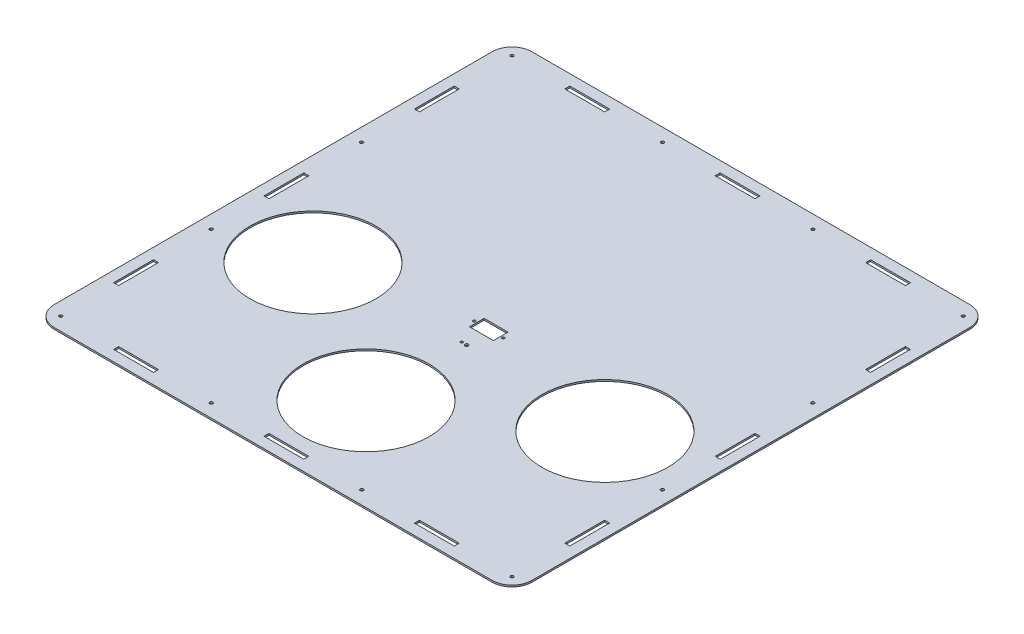
SolidWorks part; units mm, degrees
ref_plane "Front Plane" through (0, 0, 0) normal (0, 0, 1) x (1, 0, 0)
ref_plane "Top Plane" through (0, 0, 0) normal (0, 1, 0) x (1, 0, 0)
ref_plane "Right Plane" through (0, 0, 0) normal (1, 0, 0) x (0, 0, -1)
sketch "Sketch1" plane through (0, 0, 0) normal (0, 1, 0) x (1, 0, 0)
  line L1 (-228.6, -228.6) -> (228.6, -228.6)
  line L2 (-228.6, -228.6) -> (-228.6, 228.6)
  line L3 (-228.6, 228.6) -> (228.6, 228.6)
  line L4 (228.6, -228.6) -> (228.6, 228.6)
  line L5 (-228.6, -228.6) -> (228.6, 228.6) construction
  line L6 (-228.6, 228.6) -> (228.6, -228.6) construction
  point P0 (0, 0)
  dimension "D1" = 457.2
extrude "Main Plate" add sketch "Sketch1" along normal blind 1.5875
sketch "Sketch2" plane through (0, 1.5875, 0) normal (0, 1, 0) x (1, 0, 0)
  line L0 (228.6, 0) -> (-228.6, 0) construction
  line L1 (-228.6, 228.6) -> (-228.6, -228.6) construction
  line L2 (0, -228.6) -> (0, 228.6) construction
  line L3 (228.6, 228.6) -> (-228.6, 228.6) construction
  line L4 (-139.7, 228.6) -> (-139.7, -228.6) construction
  line L5 (-228.6, -228.6) -> (228.6, -228.6) construction
  circle A0 centre (0, -139.7) radius 60.325
  circle A1 centre (-139.7, -50.8) radius 60.325
  circle A3 centre (139.7, -50.8) radius 60.325
  point P6 (0, 0)
  point P12 (0, 0)
  dimension "D1" = 120.65
  dimension "D2" = 88.9
  dimension "D3" = 88.9
  dimension "D4" = 279.4
extrude "Drum Holes" cut sketch "Sketch2" against normal up to surface (1.5875 mm away) up to face at (0, 0, 0)
sketch "Sketch4" plane through (0, 1.5875, 0) normal (0, 1, 0) x (1, 0, 0)
  line L0 (-2.3813, -45.72) -> (2.3813, -45.72) construction
  line L1 (228.6, 228.6) -> (-228.6, 228.6) construction
  circle A1 centre (-139.7, -50.8) radius 60.325 construction
  circle A2 centre (-139.7, -50.8) radius 60.325 construction
  circle A6 centre (-2.3813, -45.72) radius 1.1906
  circle A7 centre (2.3813, -45.72) radius 1.5875
  point P4 (0, -45.72)
  dimension "D1" = 4.7625
  dimension "D4" = 3.175
  dimension "D2" = 2.3813
  dimension "D3" = 45.72
extrude "IR Holes" cut sketch "Sketch4" against normal up to surface (1.5875 mm away) up to face at (139.7, 0, -9.525)
sketch "Sketch5" plane through (0, 1.5875, 0) normal (0, 1, 0) x (1, 0, 0)
  line L0 (-228.6, 228.6) -> (-228.6, -228.6) construction
  line L1 (228.6, 228.6) -> (-228.6, 228.6) construction
  line L2 (-215.9, 215.9) -> (-215.9, 71.9667) construction
  line L3 (-215.9, 215.9) -> (-71.882, 215.9) construction
  line L4 (228.6, 0) -> (-228.6, 0) construction
  line L5 (0, -228.6) -> (0, 228.6) construction
  circle A0 centre (-215.9, 215.9) radius 1.4883
  circle A1 centre (-215.9, 71.9667) radius 1.4883
  circle A2 centre (-215.9, -71.9667) radius 1.4883
  circle A3 centre (-215.9, -215.9) radius 1.4883
  circle A4 centre (-71.882, 215.9) radius 1.4883
  circle A5 centre (72.136, 215.9) radius 1.4883
  circle A9 centre (215.9, 215.9) radius 1.4883
  circle A10 centre (215.9, 71.9667) radius 1.4883
  circle A11 centre (215.9, -71.9667) radius 1.4883
  circle A12 centre (215.9, -215.9) radius 1.4883
  circle A13 centre (72.136, -215.9) radius 1.4883
  circle A14 centre (-71.882, -215.9) radius 1.4883
  point P19 (0, 0)
  point P22 (0, 0)
  dimension "D1" = 2.9766
  dimension "D2" = 12.7
  dimension "D3" = 12.7
  dimension "D6" = 143.9333
  dimension "D7" = 144.018
  dimension "D4" = 4
  dimension "D5" = 3
extrude "Bolt Holes" cut sketch "Sketch5" against normal up to surface (1.5875 mm away) up to face at (-2.3813, 0, 44.5294)
sketch "Timer Strip" plane through (0, 1.5875, 0) normal (0, 1, 0) x (1, 0, 0)
  line L0 (228.6, 228.6) -> (-228.6, 228.6) construction
  line L1 (-171.45, 177.8) -> (171.45, 177.8)
  line L2 (-171.45, 177.8) -> (-171.45, 165.1)
  line L3 (-171.45, 165.1) -> (171.45, 165.1)
  line L4 (171.45, 177.8) -> (171.45, 165.1)
  line L6 (-171.45, 177.8) -> (-196.85, 177.8)
  line L7 (-171.45, 177.8) -> (-171.45, 165.1)
  line L8 (-171.45, 165.1) -> (-196.85, 165.1)
  line L9 (-196.85, 177.8) -> (-196.85, 165.1)
  point P6 (0, 228.6)
  point P7 (0, 177.8)
  dimension "D1" = 342.9
  dimension "D2" = 12.7
  dimension "D3" = 50.8
  dimension "D4" = 25.4
sketch "Sketch7" plane through (0, 1.5875, 0) normal (0, 1, 0) x (1, 0, 0)
  line L0 (-13.8906, -22.225) -> (13.8906, -22.225) construction
  line L1 (-11.43, -15.24) -> (11.43, -15.24)
  line L2 (-11.43, -15.24) -> (-11.43, -29.21)
  line L3 (-11.43, -29.21) -> (11.43, -29.21)
  line L4 (11.43, -15.24) -> (11.43, -29.21)
  circle A0 centre (-13.8906, -22.225) radius 1.1906
  circle A1 centre (13.8906, -22.225) radius 1.1906
  point P4 (0, -15.24)
  point P8 (0, -22.225)
  point P9 (-11.43, -22.225)
  dimension "D5" = 2.3813
  dimension "D1" = 22.86
  dimension "D2" = 13.97
  dimension "D3" = 15.24
  dimension "D4" = 27.7812
extrude "Servo" cut sketch "Sketch7" against normal up to surface (1.5875 mm away) up to face at (-71.882, 0, -217.3883)
extrude "Timer Hole" [suppressed] cut sketch "Timer Strip" against normal up to surface (1.5875 mm away) contours L7 L6 L9 L8
sketch "Sketch8" plane through (0, 1.5875, 0) normal (0, 1, 0) x (1, 0, 0)
  line L0 (-228.6, 228.6) -> (-228.6, -228.6) construction
  line L1 (-218.2812, -124.8833) -> (-213.5187, -124.8833)
  line L2 (-218.2812, -124.8833) -> (-218.2812, -162.9833)
  line L3 (-218.2812, -162.9833) -> (-213.5187, -162.9833)
  line L4 (-213.5187, -124.8833) -> (-213.5187, -162.9833)
  line L5 (-215.9, -71.9667) -> (-215.9, -215.9) construction
  line L10 (-215.9, -71.9667) -> (-215.9, 71.9667) construction
  line L11 (0, -228.6) -> (0, 228.6) construction
  line L12 (-218.2812, 19.05) -> (-213.5187, 19.05)
  line L13 (-218.2812, 19.05) -> (-218.2812, -19.05)
  line L14 (-218.2812, -19.05) -> (-213.5187, -19.05)
  line L15 (-213.5187, 19.05) -> (-213.5187, -19.05)
  line L16 (228.6, 228.6) -> (-228.6, 228.6) construction
  line L17 (-215.9, 215.9) -> (-215.9, 71.9667) construction
  line L18 (218.2812, -162.9833) -> (213.5187, -162.9833)
  line L19 (-218.2812, 162.9833) -> (-213.5187, 162.9833)
  line L20 (-218.2812, 162.9833) -> (-218.2812, 124.8833)
  line L21 (-218.2812, 124.8833) -> (-213.5187, 124.8833)
  line L22 (-213.5187, 162.9833) -> (-213.5187, 124.8833)
  line L23 (213.5187, -124.8833) -> (213.5187, -162.9833)
  line L24 (218.2812, -124.8833) -> (213.5187, -124.8833)
  line L25 (218.2812, -124.8833) -> (218.2812, -162.9833)
  line L26 (218.2812, -19.05) -> (213.5187, -19.05)
  line L27 (213.5187, 19.05) -> (213.5187, -19.05)
  line L28 (218.2812, 19.05) -> (213.5187, 19.05)
  line L29 (218.2812, 19.05) -> (218.2812, -19.05)
  line L30 (218.2812, 124.8833) -> (213.5187, 124.8833)
  line L31 (213.5187, 162.9833) -> (213.5187, 124.8833)
  line L32 (218.2812, 162.9833) -> (213.5187, 162.9833)
  line L33 (218.2812, 162.9833) -> (218.2812, 124.8833)
  line L34 (-215.9, 215.9) -> (-71.882, 215.9) construction
  line L35 (-71.882, 215.9) -> (72.136, 215.9) construction
  line L36 (72.136, 215.9) -> (215.9, 215.9) construction
  line L37 (228.6, 0) -> (-228.6, 0) construction
  line L38 (-162.941, 218.2812) -> (-124.841, 218.2812)
  line L39 (-162.941, 218.2812) -> (-162.941, 213.5187)
  line L40 (-162.941, 213.5187) -> (-124.841, 213.5187)
  line L41 (-124.841, 218.2812) -> (-124.841, 213.5187)
  line L42 (124.968, 218.2812) -> (163.068, 218.2812)
  line L43 (124.968, 218.2812) -> (124.968, 213.5187)
  line L44 (124.968, 213.5187) -> (163.068, 213.5187)
  line L45 (163.068, 218.2812) -> (163.068, 213.5187)
  line L46 (-19.05, 218.2812) -> (19.05, 218.2812)
  line L47 (-19.05, 218.2812) -> (-19.05, 213.5187)
  line L48 (-19.05, 213.5187) -> (19.05, 213.5187)
  line L49 (19.05, 218.2812) -> (19.05, 213.5187)
  line L50 (124.968, -213.5187) -> (163.068, -213.5187)
  line L51 (163.068, -218.2812) -> (163.068, -213.5187)
  line L52 (124.968, -218.2812) -> (163.068, -218.2812)
  line L53 (124.968, -218.2812) -> (124.968, -213.5187)
  line L54 (-19.05, -213.5188) -> (19.05, -213.5188)
  line L55 (19.05, -218.2812) -> (19.05, -213.5188)
  line L56 (-19.05, -218.2812) -> (19.05, -218.2812)
  line L57 (-19.05, -218.2812) -> (-19.05, -213.5188)
  line L58 (-162.941, -213.5188) -> (-124.841, -213.5188)
  line L59 (-124.841, -218.2813) -> (-124.841, -213.5188)
  line L60 (-162.941, -218.2813) -> (-124.841, -218.2813)
  line L61 (-162.941, -218.2813) -> (-162.941, -213.5188)
  circle A0 centre (-215.9, -215.9) radius 1.4883 construction
  circle A1 centre (-215.9, -71.9667) radius 1.4883 construction
  circle A2 centre (-215.9, -215.9) radius 1.4883 construction
  circle A3 centre (-215.9, -71.9667) radius 1.4883 construction
  circle A4 centre (-215.9, 71.9667) radius 1.4883 construction
  circle A5 centre (-215.9, 71.9667) radius 1.4883 construction
  circle A6 centre (-215.9, 215.9) radius 1.4883 construction
  circle A7 centre (-215.9, 215.9) radius 1.4883 construction
  circle A8 centre (215.9, 215.9) radius 1.4883 construction
  circle A9 centre (72.136, 215.9) radius 1.4883 construction
  circle A10 centre (-71.882, 215.9) radius 1.4883 construction
  circle A11 centre (215.9, 215.9) radius 1.4883 construction
  circle A12 centre (72.136, 215.9) radius 1.4883 construction
  circle A13 centre (-71.882, 215.9) radius 1.4883 construction
  point P12 (-215.9, -143.9333)
  point P13 (-213.5187, -143.9333)
  point P22 (-215.9, 0)
  point P23 (-215.9, 19.05)
  point P30 (0, 0)
  point P38 (-218.2812, 143.9333)
  point P73 (-143.891, 213.5187)
  point P75 (0, 218.2813)
  point P76 (144.018, 215.9)
  point P77 (144.018, 218.2812)
  point P81 (0, 0)
  point P93 (-215.9, -124.8833)
  point P96 (-218.2812, 0)
  point P97 (-215.9, 143.9333)
  point P98 (-215.9, 162.9833)
  point P99 (-143.891, 215.9)
  point P100 (-162.941, 215.9)
  point P101 (-19.05, 215.9)
  point P102 (124.968, 215.9)
  dimension "D1" = 4.7625
  dimension "D2" = 38.1
  dimension "D4" = 38.1
  dimension "D5" = 4.7625
extrude "Alignment Holes" cut sketch "Sketch8" against normal up to surface (1.5875 mm away) up to face at (-13.8906, 0, 21.0344)
fillet "Fillet1" radius 19.05 4 edges at (228.6, 0.7937, 228.6) (-228.6, 0.7937, 228.6) (228.6, 0.7937, -228.6) (-228.6, 0.7937, -228.6)
sketch "Sketch9" plane through (0, 1.5875, 0) normal (0, 1, 0) x (1, 0, 0)
  line L0 (11.43, -15.24) -> (-11.43, -15.24) construction
  line L1 (-6.35, 48.26) -> (6.35, 48.26)
  line L2 (-6.35, 48.26) -> (-6.35, 35.56)
  line L3 (-6.35, 35.56) -> (6.35, 35.56)
  line L4 (6.35, 48.26) -> (6.35, 35.56)
  point P4 (0, 35.56)
  dimension "D1" = 12.7
  dimension "D2" = 50.8
extrude "Button" [suppressed] cut sketch "Sketch9" against normal up to surface (1.5875 mm away)
equation "\"sheetthickness\"= 3 / 16"
equation "\"D5@Sketch8\"=\"sheetthickness\""
equation "\"D1@Sketch8\"=\"sheetthickness\""
